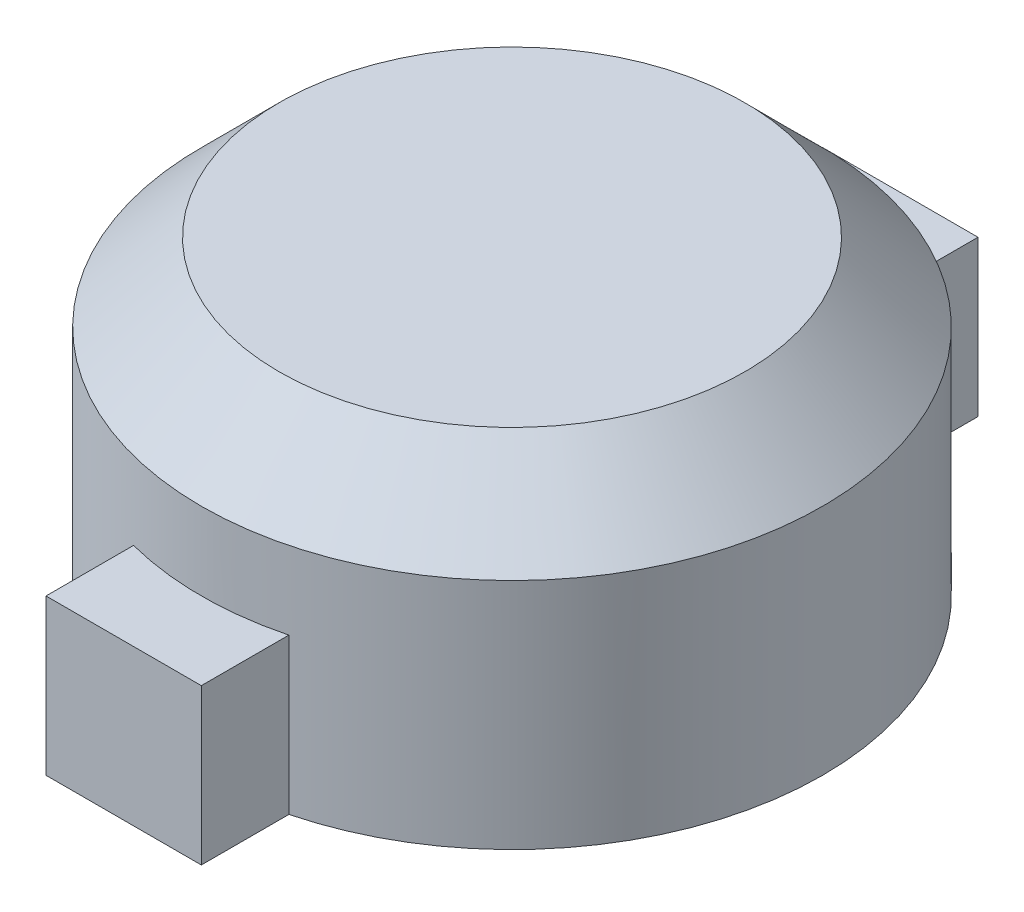
SolidWorks part; units mm, degrees
ref_plane "Front Plane" through (0, 0, 0) normal (0, 0, 1) x (1, 0, 0)
ref_plane "Top Plane" through (0, 0, 0) normal (0, 1, 0) x (1, 0, 0)
ref_plane "Right Plane" through (0, 0, 0) normal (1, 0, 0) x (0, 0, -1)
sketch "Sketch1" plane through (0, 0, 0) normal (0, 1, 0) x (1, 0, 0)
  circle A0 centre (0, 0) radius 4
  dimension "D1" = 8
extrude "Boss-Extrude1" add sketch "Sketch1" along normal blind 4
sketch "Sketch2" plane through (0, 0, 0) normal (0, -1, 0) x (1, 0, 0)
  line L1 (1, 5) -> (-1, 5)
  line L2 (1, 5) -> (1, -5)
  line L3 (1, -5) -> (-1, -5)
  line L4 (-1, 5) -> (-1, -5)
  line L5 (1, 5) -> (-1, -5) construction
  line L6 (1, -5) -> (-1, 5) construction
  point P0 (0, 0)
  dimension "D1" = 10
  dimension "D2" = 2
extrude "Boss-Extrude2" add sketch "Sketch2" against normal blind 2
chamfer "Chamfer1" distance 1 angle 45 1 edges at (0, 4, 4)
